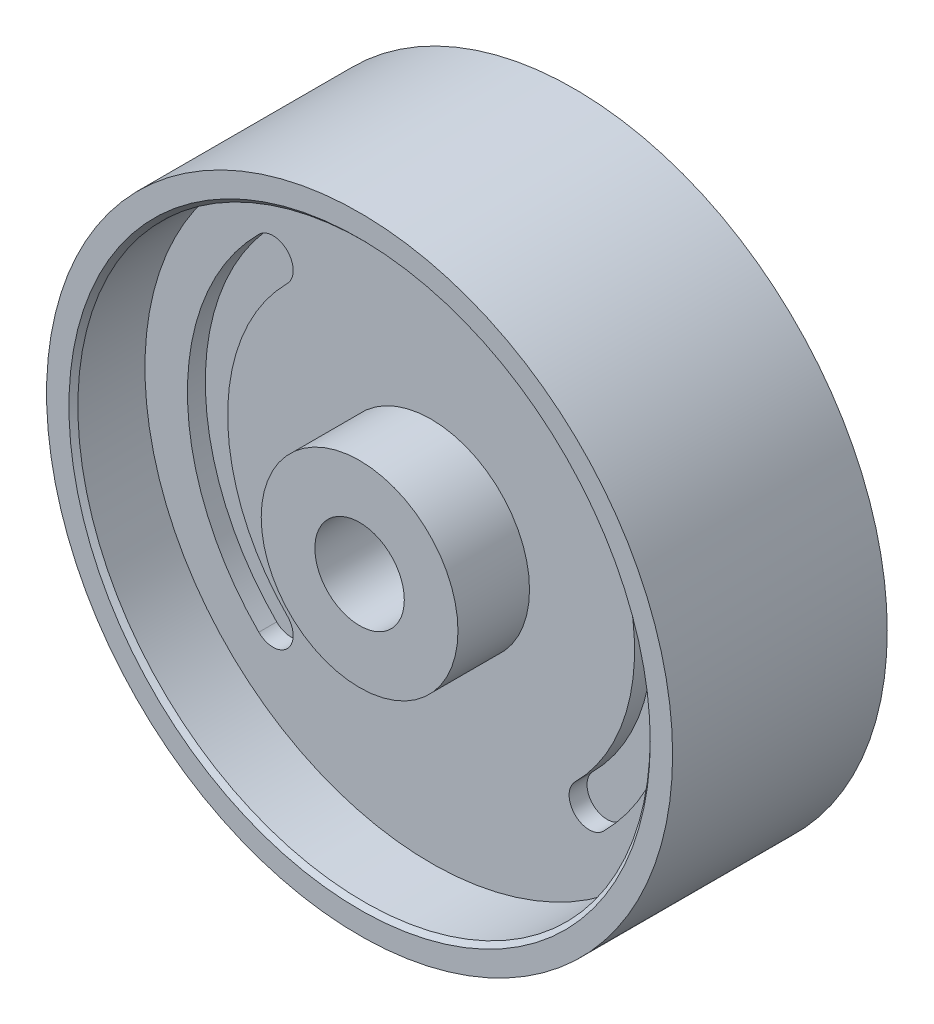
SolidWorks part; units mm, degrees
ref_plane "前视基准面" through (0, 0, 0) normal (0, 0, 1) x (1, 0, 0)
ref_plane "上视基准面" through (0, 0, 0) normal (0, 1, 0) x (1, 0, 0)
ref_plane "右视基准面" through (0, 0, 0) normal (1, 0, 0) x (0, 0, -1)
sketch "草图1" plane through (0, 0, 0) normal (0, 0, 1) x (1, 0, 0)
  circle A0 centre (0, 0) radius 35
  dimension "D1" = 70
extrude "凸台-拉伸1" add sketch "草图1" along normal mid plane 24
sketch "草图2" plane through (0, 0, 0) normal (0, 0, 1) x (1, 0, 0)
  circle A0 centre (0, 0) radius 5
  dimension "D1" = 10
extrude "切除-拉伸1" cut sketch "草图2" along normal through all both and the other way through all
sketch "草图3" plane through (0, 0, 12) normal (0, 0, 1) x (1, 0, 0)
  circle A0 centre (0, 0) radius 32
  circle A1 centre (0, 0) radius 11
  dimension "D1" = 64
  dimension "D2" = 22
extrude "切除-拉伸2" cut sketch "草图3" against normal blind 8
sketch "草图4" plane through (0, 0, 4) normal (0, 0, 1) x (1, 0, 0)
  line L0 (0, 0) -> (-29.5589, 29.5589) construction
  line L1 (0, 0) -> (-47.3123, 0) construction
  line L2 (0, 0) -> (-29.5589, -29.5589) construction
  line L3 (0, 0) -> (0, -23.7741) construction
  arc A0 (-17.6777, 17.6777) -> (-17.6777, -17.6777) centre (0, 0) ccw construction
  arc A1 (-19.2687, 19.2687) -> (-19.2687, -19.2687) centre (0, 0) ccw
  arc A2 (-16.0867, 16.0867) -> (-16.0867, -16.0867) centre (0, 0) ccw
  arc A3 (-16.0867, 16.0867) -> (-19.2687, 19.2687) centre (-17.6777, 17.6777) ccw
  arc A4 (-19.2687, -19.2687) -> (-16.0867, -16.0867) centre (-17.6777, -17.6777) ccw
  arc A5 (17.6777, 17.6777) -> (17.6777, -17.6777) centre (0, 0) cw construction
  arc A6 (19.2687, 19.2687) -> (19.2687, -19.2687) centre (0, 0) cw
  arc A7 (16.0867, 16.0867) -> (16.0867, -16.0867) centre (0, 0) cw
  arc A8 (16.0867, 16.0867) -> (19.2687, 19.2687) centre (17.6777, 17.6777) cw
  arc A9 (19.2687, -19.2687) -> (16.0867, -16.0867) centre (17.6777, -17.6777) cw
  point P4 (-25, 0)
  point P16 (25, 0)
  dimension "D1" = 25
  dimension "D2" = 2.25
  dimension "D3" = 90
extrude "切除-拉伸3" cut sketch "草图4" against normal blind 2
mirror "镜向1" about plane through (0, 0, 0) normal (0, 0, 1) of "切除-拉伸3", "切除-拉伸2"
chamfer "倒角1" distance 0.5 angle 45 2 edges at (32, 0, 12) (32, 0, -12)
